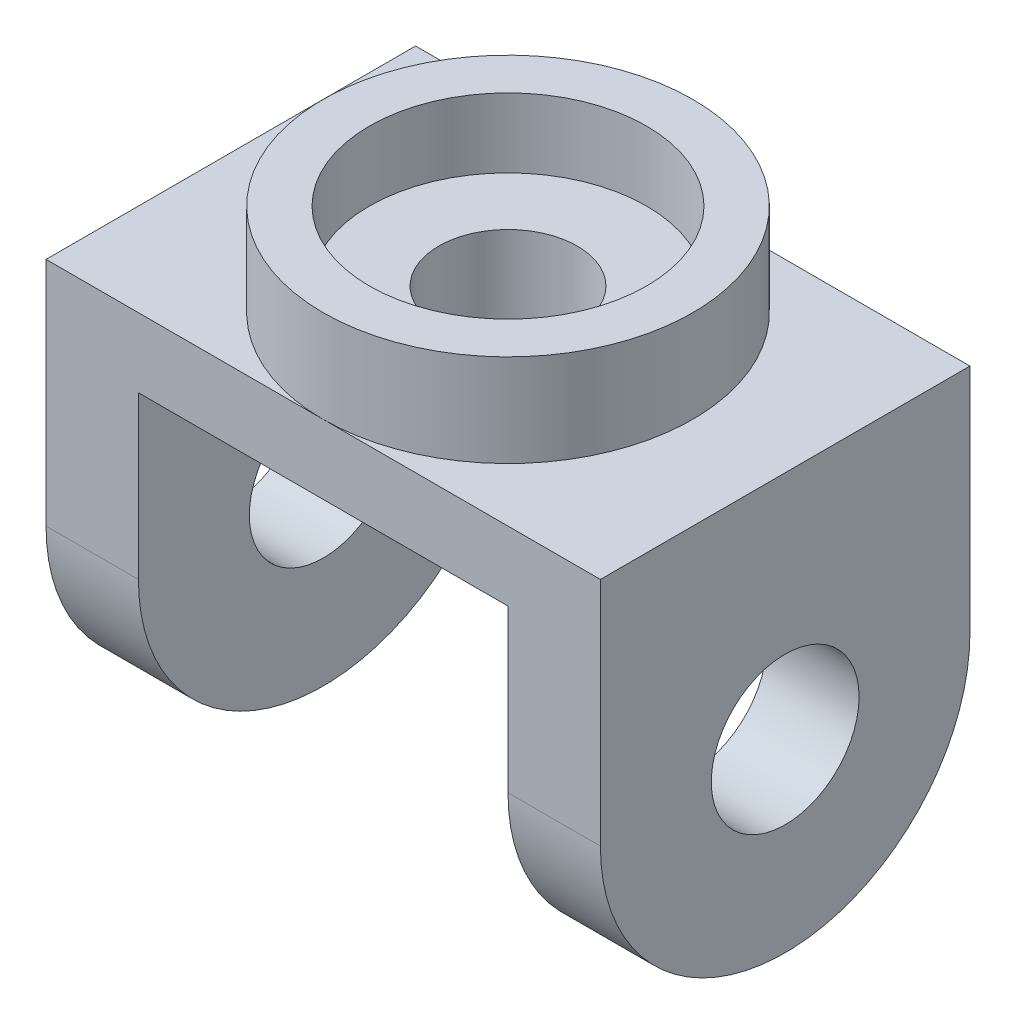
SolidWorks part; units mm, degrees
ref_plane "Front Plane" through (0, 0, 0) normal (0, 0, 1) x (1, 0, 0)
ref_plane "Top Plane" through (0, 0, 0) normal (0, 1, 0) x (1, 0, 0)
ref_plane "Right Plane" through (0, 0, 0) normal (1, 0, 0) x (0, 0, -1)
sketch "Sketch1" plane through (0, 0, 0) normal (0, 1, 0) x (1, 0, 0)
  line L1 (60, -40) -> (-60, -40)
  line L2 (60, -40) -> (60, 40)
  line L3 (60, 40) -> (-60, 40)
  line L4 (-60, -40) -> (-60, 40)
  line L5 (60, -40) -> (-60, 40) construction
  line L6 (60, 40) -> (-60, -40) construction
  point P0 (0, 0)
  dimension "D1" = 80
  dimension "D2" = 120
extrude "Boss-Extrude1" add sketch "Sketch1" against normal blind 15
sketch "Sketch2" plane through (0, 0, 0) normal (0, 1, 0) x (1, 0, 0)
  circle A0 centre (0, 0) radius 40
  dimension "D1" = 80
extrude "Boss-Extrude2" add sketch "Sketch2" along normal blind 20
sketch "Sketch4" plane through (0, 20, 0) normal (0, 1, 0) x (1, 0, 0)
  circle A0 centre (0, 0) radius 30
  dimension "D1" = 60
extrude "Cut-Extrude1" cut sketch "Sketch4" against normal blind 15
sketch "Sketch5" plane through (0, 5, 0) normal (0, 1, 0) x (1, 0, 0)
  circle A0 centre (0, 0) radius 15
  dimension "D1" = 30
extrude "Cut-Extrude2" cut sketch "Sketch5" against normal blind 42
sketch "Sketch7" plane through (60, 0, 0) normal (1, 0, 0) x (0, 0, -1)
  line L0 (40, -15) -> (40, 0) construction
  line L1 (-40, 0) -> (40, 0)
  line L2 (-40, 0) -> (-40, -50)
  line L3 (-40, -50) -> (40, -50)
  line L4 (40, 0) -> (40, -50)
  arc A0 (-40, -50) -> (40, -50) centre (0, -50) ccw
  line M6 (-40, -15) -> (40, -15)
  dimension "D1" = 50
extrude "Boss-Extrude3" add sketch "Sketch7" against normal blind 20 contours L3 A0 | L4 L2 L3 M6
sketch "Sketch8" plane through (-60, 0, 0) normal (-1, 0, 0) x (0, 0, 1)
  line L0 (40, -15) -> (40, -50) construction
  line L1 (-40, 0) -> (40, 0)
  line L2 (-40, 0) -> (-40, -50)
  line L3 (-40, -50) -> (40, -50)
  line L4 (40, 0) -> (40, -50)
  arc A0 (-40, -50) -> (40, -50) centre (0, -50) ccw
  line M3 (-40, -15) -> (40, -15)
extrude "Boss-Extrude4" add sketch "Sketch8" against normal blind 20 contours L3 A0 | L4 L2 L3 M3
sketch "Sketch9" plane through (-60, 0, 0) normal (-1, 0, 0) x (0, 0, 1)
  line L0 (0, 0) -> (0, -95.6475) construction
  line L1 (40, -50) -> (-40, -50) construction
  circle A0 centre (0, -50) radius 16
  dimension "D1" = 32
extrude "Cut-Extrude3" cut sketch "Sketch9" against normal blind 139
